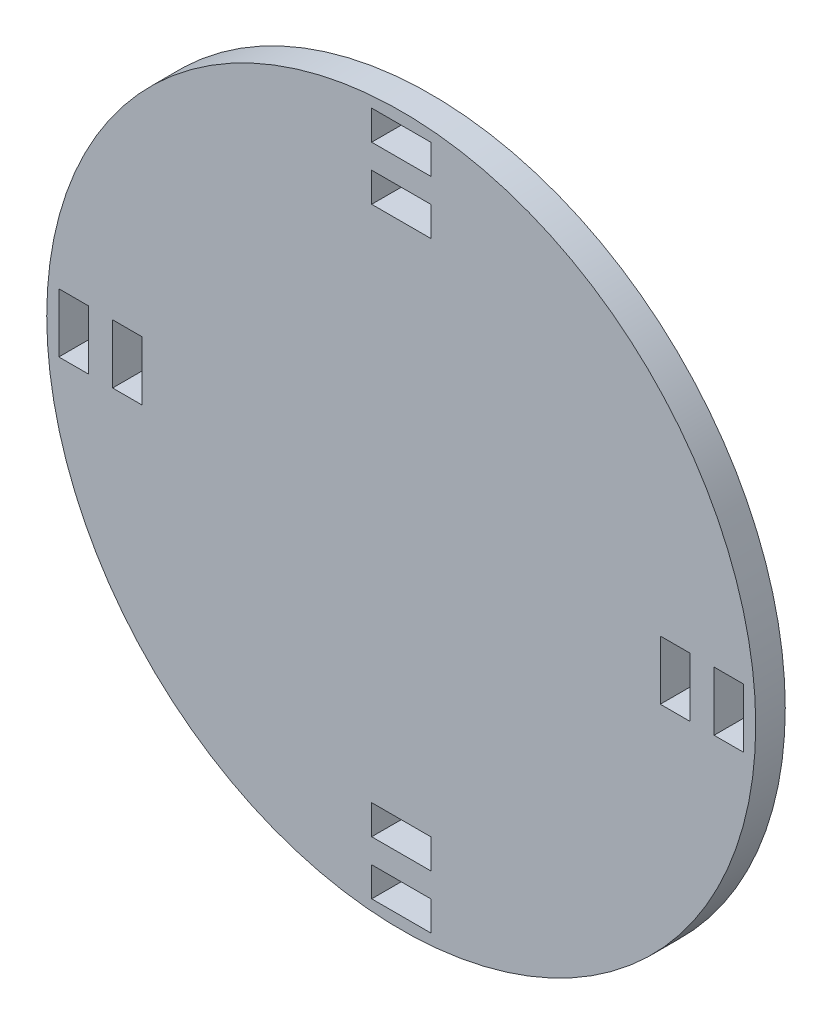
SolidWorks part; units mm, degrees
ref_plane "Front Plane" through (0, 0, 0) normal (0, 0, 1) x (1, 0, 0)
ref_plane "Top Plane" through (0, 0, 0) normal (0, 1, 0) x (1, 0, 0)
ref_plane "Right Plane" through (0, 0, 0) normal (1, 0, 0) x (0, 0, -1)
sketch "Sketch1" plane through (0, 0, 0) normal (0, 0, 1) x (1, 0, 0)
  circle A0 centre (0, 0) radius 53.086
  circle A5 centre (0, 0) radius 76.2
  point P23 (0, 0)
  dimension "D1" = 106.172
  dimension "D2" = 152.4
extrude "Boss-Extrude2" add sketch "Sketch1" along normal blind 6.35
sketch "Sketch2" plane through (0, 0, 6.35) normal (0, 0, 1) x (1, 0, 0)
  line L0 (0, 0) -> (0, 76.2) construction
  line L1 (-6.35, 73.5965) -> (6.35, 73.5965)
  line L2 (-6.35, 73.5965) -> (-6.35, 67.2465)
  line L3 (-6.35, 67.2465) -> (6.35, 67.2465)
  line L4 (6.35, 73.5965) -> (6.35, 67.2465)
  line L5 (-6.35, 62.0395) -> (6.35, 62.0395)
  line L6 (-6.35, 62.0395) -> (-6.35, 55.6895)
  line L7 (-6.35, 55.6895) -> (6.35, 55.6895)
  line L8 (6.35, 62.0395) -> (6.35, 55.6895)
  line L9 (0, 64.643) -> (0, 53.086) construction
  line L10 (-6.35, 62.0395) -> (6.35, 55.6895) construction
  line L11 (0, 76.2) -> (0, 64.643) construction
  line L12 (-6.35, 73.5965) -> (6.35, 67.2465) construction
  circle A0 centre (0, 0) radius 64.643 construction
  circle A1 centre (0, 0) radius 76.2 construction
  circle A2 centre (0, 0) radius 53.086 construction
  circle A3 centre (0, 0) radius 76.2 construction
  circle A4 centre (0, 0) radius 53.086 construction
  point P20 (0, 58.8645)
  point P21 (0, 58.8645)
  point P22 (0, 70.4215)
  point P23 (0, 70.4215)
  dimension "D5" = 129.286
  dimension "D6" = 152.4
  dimension "D7" = 106.172
  dimension "D1" = 6.35
  dimension "D2" = 12.7
  dimension "D3" = 6.35
  dimension "D4" = 12.7
extrude "Cut-Extrude1" cut sketch "Sketch2" against normal up to next
pattern_circular "CirPattern1" count 4 over 360 about axis through (0, 0, 0) along (0, 0, 1) of "Cut-Extrude1"
sketch "Sketch3" plane through (0, 0, 6.35) normal (0, 0, 1) x (1, 0, 0)
  circle A0 centre (0, 0) radius 53.086 construction
  circle A1 centre (0, 0) radius 53.086
extrude "Boss-Extrude3" add sketch "Sketch3" against normal up to surface (6.35 mm away) up to face at (-70.4215, 0, 0)
equation "\"D5@Sketch2\"=(\"D6@Sketch2\"+\"D7@Sketch2\")/2"
